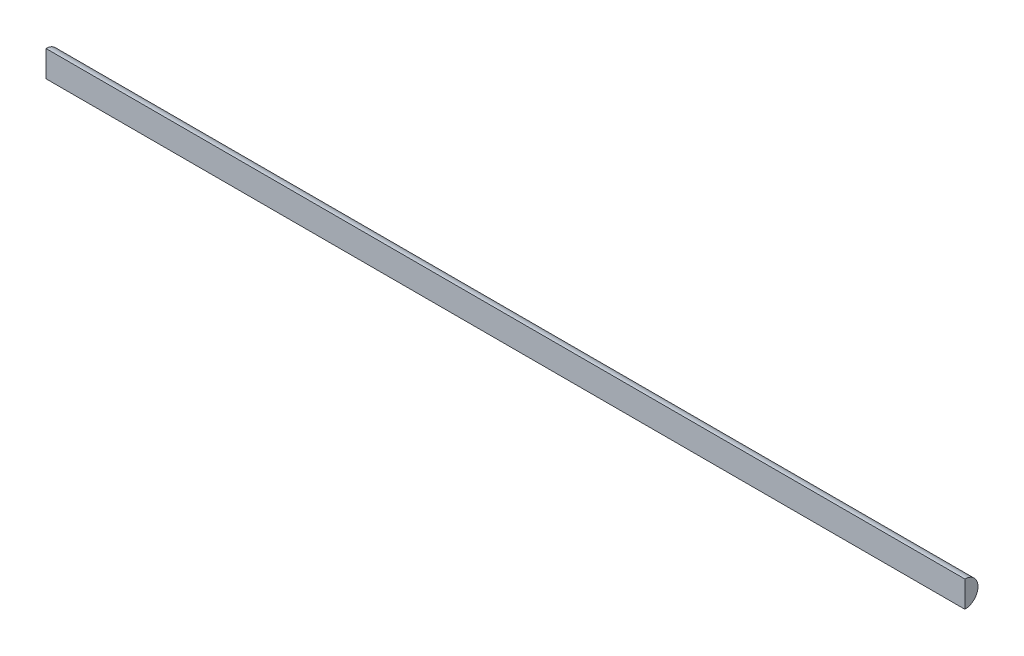
SolidWorks part; units mm, degrees
ref_plane "Front Plane" through (0, 0, 0) normal (0, 0, 1) x (1, 0, 0)
ref_plane "Top Plane" through (0, 0, 0) normal (0, 1, 0) x (1, 0, 0)
ref_plane "Right Plane" through (0, 0, 0) normal (1, 0, 0) x (0, 0, -1)
sketch "Sketch1" plane through (0, 0, 0) normal (1, 0, 0) x (0, 0, -1)
  line L0 (0, 0.5) -> (0, -0.5)
  arc A0 (0, -0.5) -> (0, 0.5) centre (0, 0) ccw
  dimension "D1" = 1
extrude "Boss-Extrude1" add sketch "Sketch1" along normal blind 35
